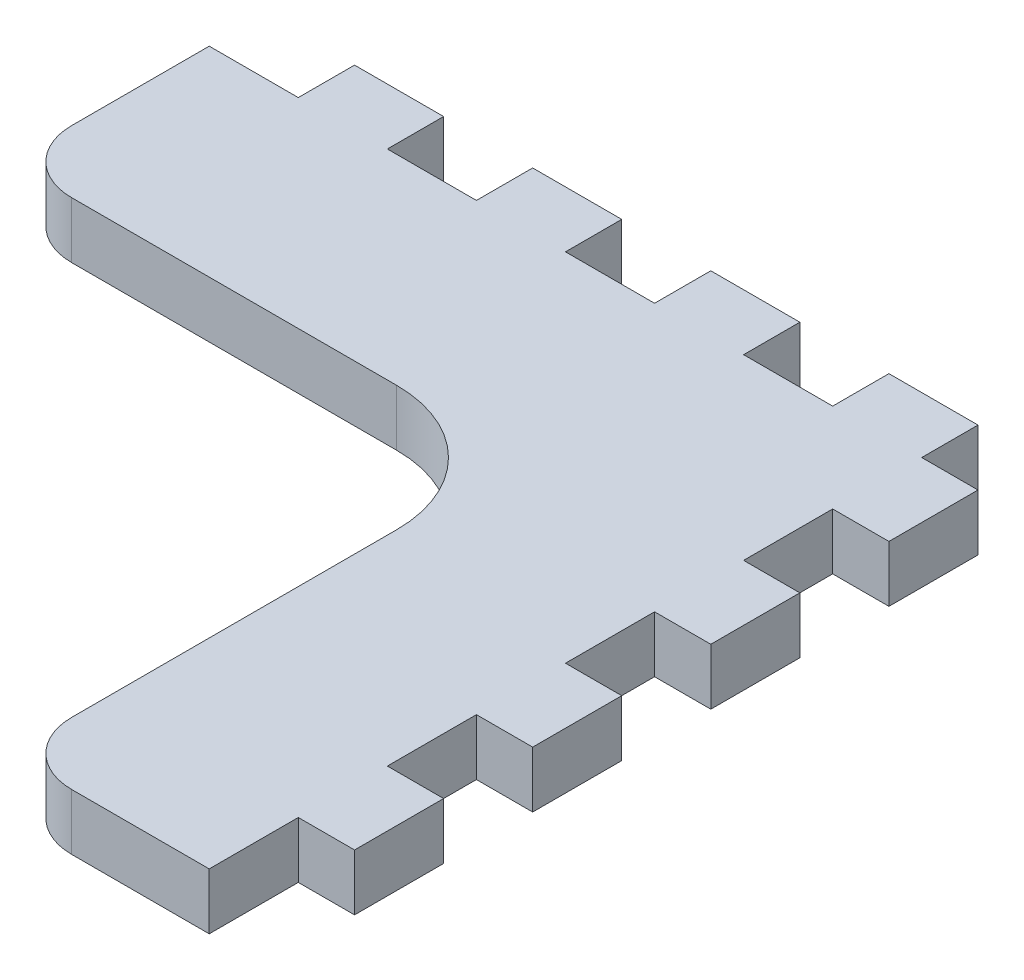
SolidWorks part; units mm, degrees
ref_plane "前视基准面" through (0, 0, 0) normal (0, 0, 1) x (1, 0, 0)
ref_plane "上视基准面" through (0, 0, 0) normal (0, 1, 0) x (1, 0, 0)
ref_plane "右视基准面" through (0, 0, 0) normal (1, 0, 0) x (0, 0, -1)
sketch "草图1" plane through (0, 0, 0) normal (0, 1, 0) x (1, 0, 0)
  line L0 (23.6808, 18.7997) -> (23.6808, 11.6747)
  line L1 (23.6808, 4.5497) -> (23.6808, -2.5753)
  line L2 (23.6808, -9.7003) -> (23.6808, -16.8253)
  line L3 (23.6808, -23.9503) -> (23.6808, -31.0753)
  line L4 (19.1808, -38.2003) -> (19.1808, -31.0753)
  line L5 (19.1808, -23.9503) -> (19.1808, -16.8253)
  line L6 (19.1808, -9.7003) -> (19.1808, -2.5753)
  line L7 (19.1808, 4.5497) -> (19.1808, 11.6747)
  line L8 (23.6808, 18.7997) -> (19.1808, 18.7997)
  line L9 (-32.8192, 2.7997) -> (-6.8192, 2.7997)
  line L10 (3.1808, -33.2003) -> (3.1808, -7.2003)
  line L11 (8.1808, -38.2003) -> (19.1808, -38.2003)
  line L12 (-37.8192, 7.7997) -> (-37.8192, 18.7997)
  line L13 (19.1808, -9.7003) -> (23.6808, -9.7003)
  line L14 (23.6808, 4.5497) -> (19.1808, 4.5497)
  line L15 (19.1808, -2.5753) -> (23.6808, -2.5753)
  line L16 (19.1808, 11.6747) -> (23.6808, 11.6747)
  line L17 (23.6808, -23.9503) -> (19.1808, -23.9503)
  line L18 (19.1808, -16.8253) -> (23.6808, -16.8253)
  line L19 (19.1808, -31.0753) -> (23.6808, -31.0753)
  line L20 (19.1808, 23.2997) -> (12.0558, 23.2997)
  line L21 (4.9308, 23.2997) -> (-2.1942, 23.2997)
  line L22 (-9.3192, 23.2997) -> (-16.4442, 23.2997)
  line L23 (-23.5692, 23.2997) -> (-30.6942, 23.2997)
  line L24 (-37.8192, 18.7997) -> (-30.6942, 18.7997)
  line L25 (-23.5692, 18.7997) -> (-16.4442, 18.7997)
  line L26 (-9.3192, 18.7997) -> (-2.1942, 18.7997)
  line L27 (4.9308, 18.7997) -> (12.0558, 18.7997)
  line L28 (-9.3192, 18.7997) -> (-9.3192, 23.2997)
  line L29 (4.9308, 23.2997) -> (4.9308, 18.7997)
  line L30 (-2.1942, 18.7997) -> (-2.1942, 23.2997)
  line L31 (12.0558, 18.7997) -> (12.0558, 23.2997)
  line L32 (-23.5692, 23.2997) -> (-23.5692, 18.7997)
  line L33 (-16.4442, 18.7997) -> (-16.4442, 23.2997)
  line L34 (-30.6942, 18.7997) -> (-30.6942, 23.2997)
  line L35 (19.1808, 23.2997) -> (19.1808, 18.7997)
  arc A0 (3.1808, -7.2003) -> (-6.8192, 2.7997) centre (-6.8192, -7.2003) ccw
  arc A1 (3.1808, -33.2003) -> (8.1808, -38.2003) centre (8.1808, -33.2003) ccw
  arc A2 (-37.8192, 7.7997) -> (-32.8192, 2.7997) centre (-32.8192, 7.7997) ccw
extrude "凸台-拉伸1" add sketch "草图1" along normal blind 4.5 contours A0 L9 A2 L12 L24 L34 L23 L32 L25 L33 L22 L28 L26 L30 L21 L29 L27 L31 L20 L35 L8 L0 L16 L7 L14 L1 L15 L6 L13 L2 L18 L5 L17 L3 L19 L4 L11 A1 L10
